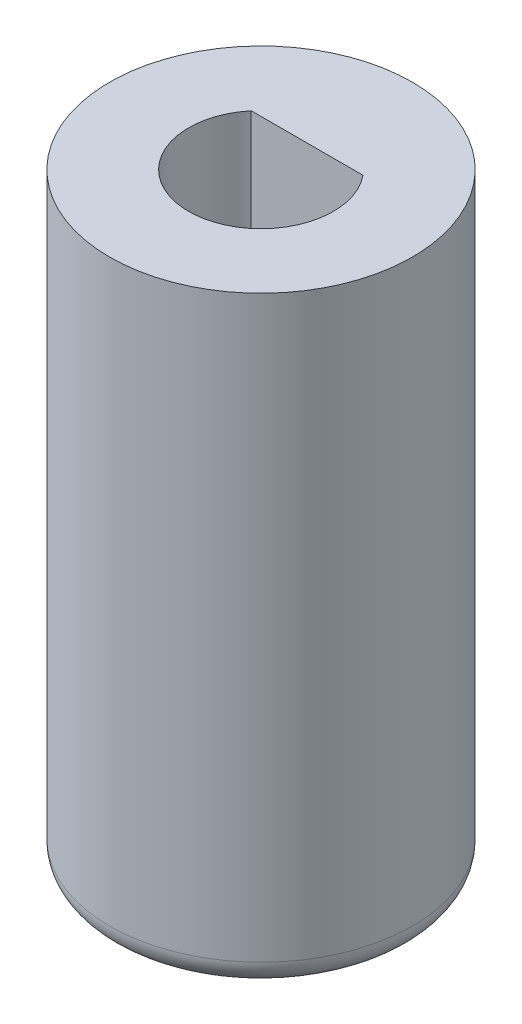
SolidWorks part; units mm, degrees
ref_plane "Front Plane" through (0, 0, 0) normal (0, 0, 1) x (1, 0, 0)
ref_plane "Top Plane" through (0, 0, 0) normal (0, 1, 0) x (1, 0, 0)
ref_plane "Right Plane" through (0, 0, 0) normal (1, 0, 0) x (0, 0, -1)
sketch "Sketch1" plane through (0, 0, 0) normal (0, 1, 0) x (1, 0, 0)
  circle A0 centre (0, 0) radius 5.75
  circle A1 centre (0, 0) radius 2.75
  dimension "D1" = 11.5
  dimension "D2" = 5.5
extrude "Boss-Extrude1" add sketch "Sketch1" along normal blind 20
sketch "Sketch5" plane through (0, 20, 0) normal (0, 1, 0) x (1, 0, 0)
  line L0 (-2.1213, 1.75) -> (2.1213, 1.75)
  line L1 (-6.325, 0) -> (6.325, 0) construction
  circle A0 centre (0, 0) radius 2.75 construction
  arc A1 (2.1213, 1.75) -> (-2.1213, 1.75) centre (0, 0) ccw
  dimension "D1" = 1.75
extrude "Boss-Extrude3" add sketch "Sketch5" against normal up to surface (20 mm away) up to plane "Top Plane"
sketch "Sketch2" plane through (0, 0, 0) normal (0, 0, 1) x (1, 0, 0)
  line L0 (0, -6.325) -> (0, 6.325) construction
  line L1 (2.75, 20) -> (-2.75, 20) construction
  circle A0 centre (0, 10) radius 1.1
  dimension "D1" = 2.2
  dimension "D2" = 10
extrude "Cut-Extrude1" cut sketch "Sketch2" against normal through all
sketch "Sketch3" plane through (0, 0, 0) normal (0, -1, 0) x (1, 0, 0)
  circle A0 centre (0, 0) radius 5.75 construction
  circle A1 centre (0, 0) radius 5.75
extrude "Boss-Extrude2" add sketch "Sketch3" along normal blind 3
fillet "Fillet1" radius 1 1 edges at (0, -3, -5.75)
